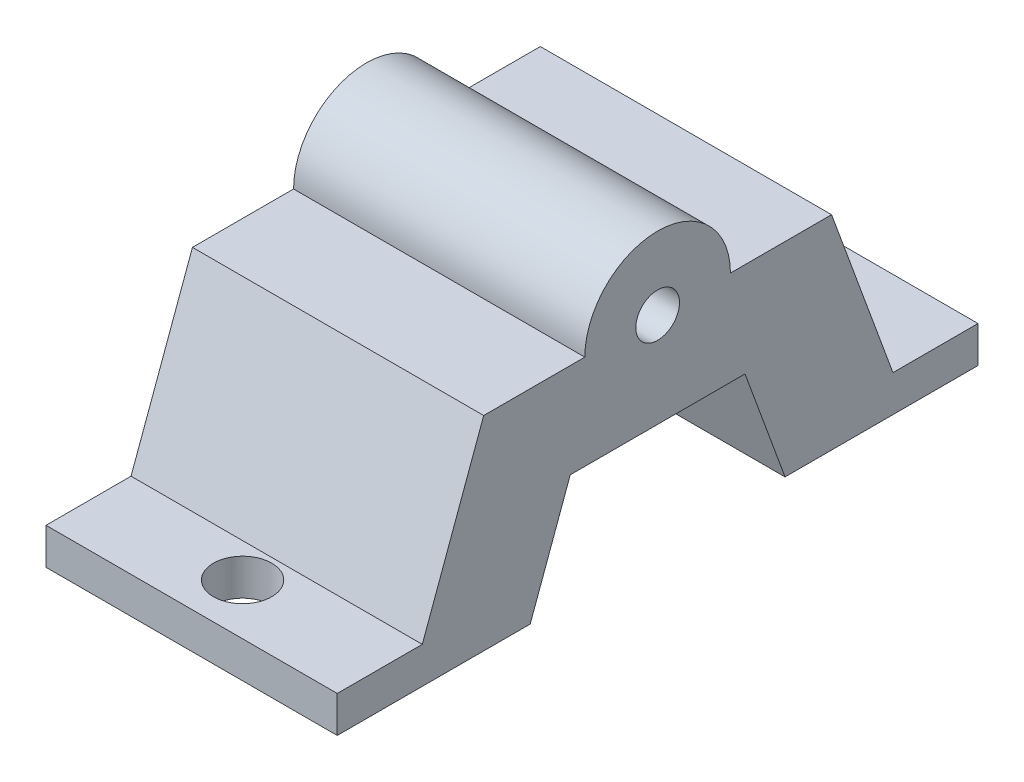
SolidWorks part; units mm, degrees
ref_plane "Front Plane" through (0, 0, 0) normal (0, 0, 1) x (1, 0, 0)
ref_plane "Top Plane" through (0, 0, 0) normal (0, 1, 0) x (1, 0, 0)
ref_plane "Right Plane" through (0, 0, 0) normal (1, 0, 0) x (0, 0, -1)
sketch "Sketch1" plane through (0, 0, 0) normal (1, 0, 0) x (0, 0, -1)
  line L0 (-24.0972, 0) -> (-24.0972, 5)
  line L1 (-24.0972, 5) -> (-12.4184, 5)
  line L2 (-12.4184, 5) -> (-3.985, 28)
  line L3 (-3.985, 28) -> (9.9028, 28)
  line L4 (-24.0972, 0) -> (2.4028, 0)
  line L5 (2.4028, 0) -> (7.9028, 15)
  line L6 (7.9028, 15) -> (31.9028, 15)
  line L7 (31.9028, 15) -> (37.4028, 0)
  line L8 (37.4028, 0) -> (63.9028, 0)
  line L9 (63.9028, 0) -> (63.9028, 5)
  line L10 (63.9028, 5) -> (52.2239, 5)
  line L11 (52.2239, 5) -> (43.7906, 28)
  line L12 (43.7906, 28) -> (29.9028, 28)
  arc A0 (9.9028, 28) -> (29.9028, 28) centre (19.9028, 28) cw
  circle A1 centre (19.9028, 28) radius 3
  dimension "D7" = 10
  dimension "D1" = 88
  dimension "D2" = 35
  dimension "D3" = 5
  dimension "D4" = 28
  dimension "D5" = 24
  dimension "D6" = 15
extrude "Boss-Extrude1" add sketch "Sketch1" against normal blind 40
sketch "Sketch2" plane through (0, 5, 0) normal (0, 1, 0) x (1, 0, 0)
  line L0 (0, -12.4184) -> (0, -24.0972) construction
  line L1 (-40, -24.0972) -> (0, -24.0972) construction
  line L2 (0, 63.9028) -> (0, 52.2239) construction
  line L3 (-40, 63.9028) -> (0, 63.9028) construction
  circle A0 centre (-20, -17.0972) radius 4
  circle A1 centre (-20, 56.9028) radius 4
  dimension "D1" = 20
  dimension "D2" = 7
  dimension "D3" = 20
  dimension "D4" = 7
extrude "Cut-Extrude1" cut sketch "Sketch2" against normal blind 40
